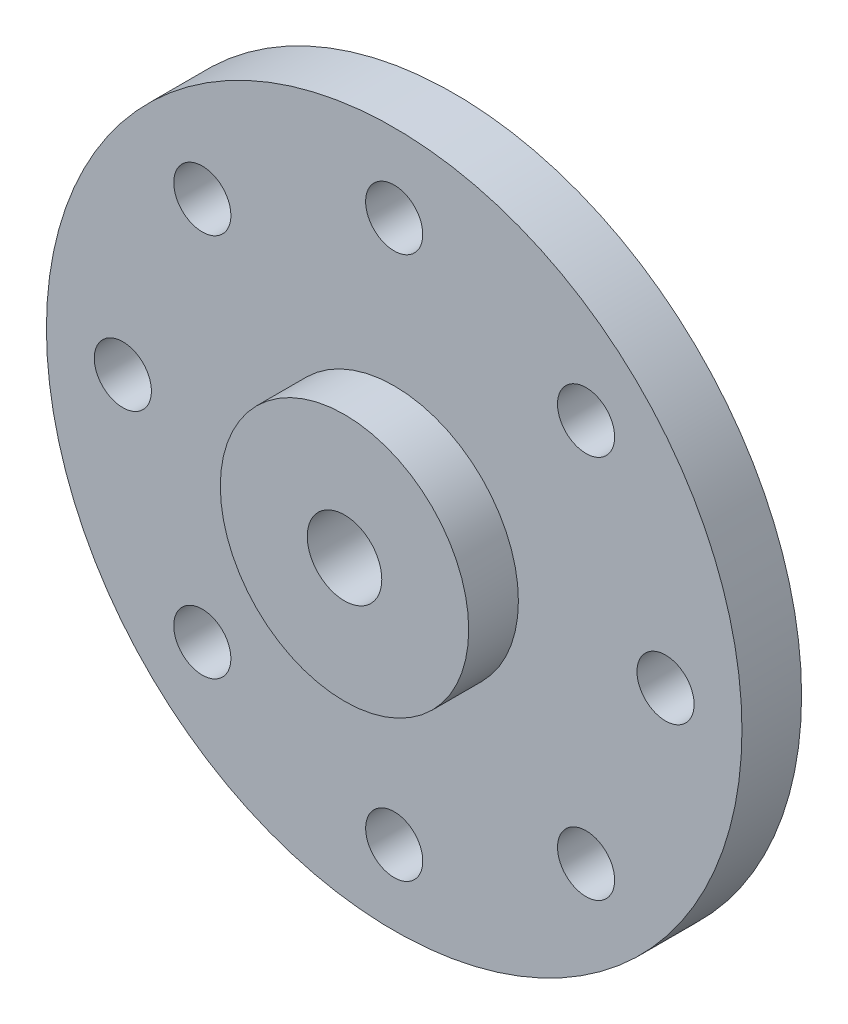
SolidWorks part; units mm, degrees
ref_plane "Front Plane" through (0, 0, 0) normal (0, 0, 1) x (1, 0, 0)
ref_plane "Top Plane" through (0, 0, 0) normal (0, 1, 0) x (1, 0, 0)
ref_plane "Right Plane" through (0, 0, 0) normal (1, 0, 0) x (0, 0, -1)
sketch "Sketch1" plane through (0, 0, 0) normal (0, 0, 1) x (1, 0, 0)
  circle A0 centre (0, 0) radius 14
  dimension "D1" = 28
extrude "Boss-Extrude1" add sketch "Sketch1" along normal blind 2.4
sketch "Sketch2" plane through (0, 0, 2.4) normal (0, 0, 1) x (1, 0, 0)
  circle A0 centre (0, 0) radius 2.8487
  circle A1 centre (0, 10.85) radius 1.15
extrude "Cut-Extrude1" cut sketch "Sketch2" against normal through all
pattern_circular "CirPattern2" count 8 every 45 about axis through (0, -0.0737, 0) along (0, 0, 1) of "Cut-Extrude1"
sketch "Sketch4" plane through (0, 0, 2.4) normal (0, 0, 1) x (1, 0, 0)
  circle A0 centre (0, 0) radius 5
  dimension "D1" = 10
extrude "Boss-Extrude2" add sketch "Sketch4" along normal blind 2
sketch "Sketch5" plane through (0, 0, 4.4) normal (0, 0, 1) x (1, 0, 0)
  circle A0 centre (0, 0) radius 1.5
  dimension "D1" = 3
extrude "Cut-Extrude3" cut sketch "Sketch5" against normal through all
